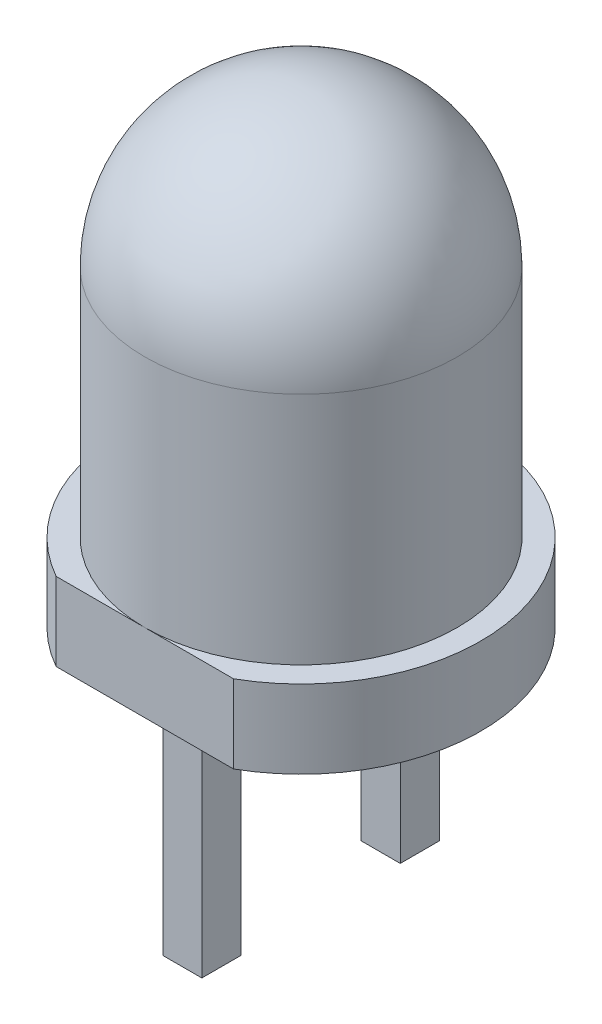
SolidWorks part; units mm, degrees
ref_plane "Спереди" through (0, 0, 0) normal (0, 0, 1) x (1, 0, 0)
ref_plane "Сверху" through (0, 0, 0) normal (0, 1, 0) x (1, 0, 0)
ref_plane "Справа" through (0, 0, 0) normal (1, 0, 0) x (0, 0, -1)
sketch "Эскиз1" plane through (0, 0, 0) normal (0, 1, 0) x (1, 0, 0)
  circle A0 centre (0, 0) radius 2.3
extrude "Бобышка-Вытянуть1" add sketch "Эскиз1" along normal blind 1 contours A0
sketch "Эскиз2" plane through (0, 1, 0) normal (0, 1, 0) x (1, 0, 0)
  circle A0 centre (0, 0) radius 2
extrude "Бобышка-Вытянуть2" add sketch "Эскиз2" along normal blind 5 contours A0
sketch "Эскиз3" plane through (0, 0, 0) normal (0, -1, 0) x (1, 0, 0)
  line L0 (0, 0) -> (0, 1.27) construction
  line L2 (0.25, 1.02) -> (-0.25, 1.02)
  line L3 (0.25, 1.02) -> (0.25, 1.52)
  line L4 (0.25, 1.52) -> (-0.25, 1.52)
  line L5 (-0.25, 1.02) -> (-0.25, 1.52)
  line L6 (0.25, 1.02) -> (-0.25, 1.52) construction
  line L7 (0.25, 1.52) -> (-0.25, 1.02) construction
extrude "Бобышка-Вытянуть3" add sketch "Эскиз3" along normal blind 3 contours L4 L5 L2 L3
ref_plane "Плоскость1" through (0, 0, 0) normal (0, 0, -1) x (-1, 0, 0)
mirror "Зеркальное отражение1" about plane through (0, 0, 0) normal (0, 0, -1) of "Бобышка-Вытянуть3"
ref_plane "Плоскость2" through (0, 0, 2) normal (0, 0, 1) x (1, 0, 0)
sketch "Эскиз4" plane through (0, 0, 2) normal (0, 0, 1) x (1, 0, 0)
  line L1 (4.7171, -9.726) -> (-4.7171, -9.726)
  line L2 (4.7171, -9.726) -> (4.7171, 9.726)
  line L3 (4.7171, 9.726) -> (-4.7171, 9.726)
  line L4 (-4.7171, -9.726) -> (-4.7171, 9.726)
  line L5 (4.7171, -9.726) -> (-4.7171, 9.726) construction
  line L6 (4.7171, 9.726) -> (-4.7171, -9.726) construction
  point P0 (0, 0)
extrude "Вырез-Вытянуть1" cut sketch "Эскиз4" along normal blind 3 contours L3 L4 L1 L2
fillet "Скругление1" radius 2 1 edges at (0, 6, 2)
